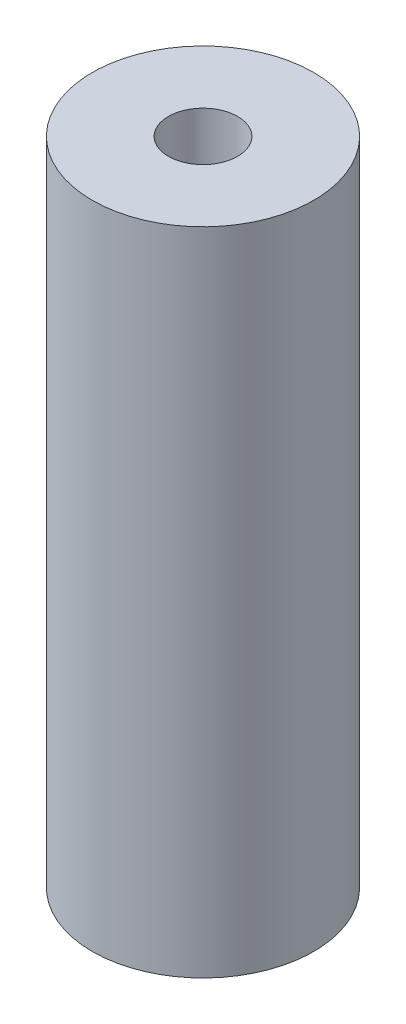
SolidWorks part; units mm, degrees
ref_plane "前视基准面" through (0, 0, 0) normal (0, 0, 1) x (1, 0, 0)
ref_plane "上视基准面" through (0, 0, 0) normal (0, 1, 0) x (1, 0, 0)
ref_plane "右视基准面" through (0, 0, 0) normal (1, 0, 0) x (0, 0, -1)
sketch "草图1" plane through (0, 0, 0) normal (0, 1, 0) x (1, 0, 0)
  circle A0 centre (0, 0) radius 4
extrude "凸台-拉伸3" add sketch "草图1" along normal blind 23.5 contours A0
sketch "草图5" plane through (0, 0, 0) normal (0, -1, 0) x (1, 0, 0)
  point P0 (0, 0)
hole_wizard "M3 螺纹孔1" positions "草图6" profile "草图7" tap size "M3" standard "GB" end condition through all
sketch "草图6" plane through (0, 0, 0) normal (0, -1, 0) x (-1, 0, 0)
  point P0 (0, 0)
cosmetic thread "孔螺蚊线2"
sketch "草图7" plane through (0, 0, 0) normal (1, 0, 0) x (0, 0, -1)
  line L0 (0, 0) -> (0, 23.5)
  line L1 (0, 23.5) -> (1.25, 23.5)
  line L2 (1.25, 23.5) -> (1.25, 0)
  line L5 (1.25, 0) -> (0, 0)
  line L11 (0, -6.35) -> (0, 107.95) construction
  dimension "通孔螺纹孔钻头直径" = 2.5
  dimension "通孔螺纹孔钻头深度" = 23.5
